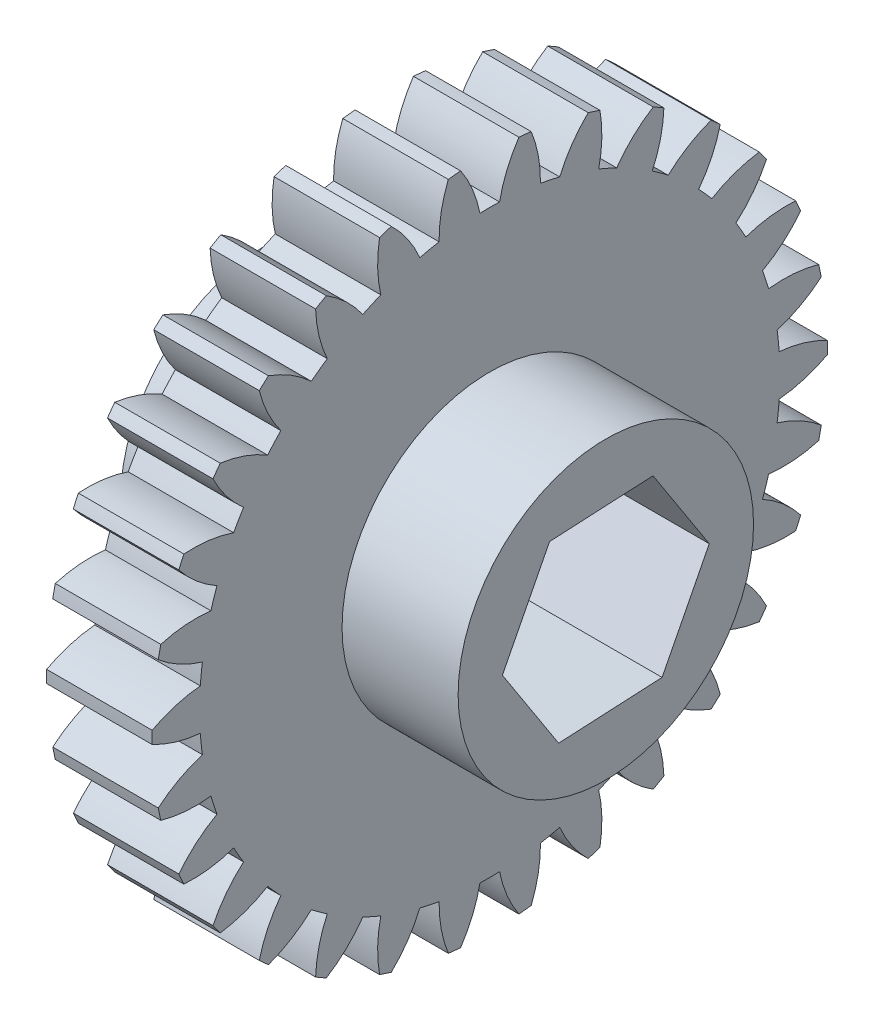
SolidWorks part; units mm, degrees
ref_plane "Plane1" through (0, 0, 0) normal (0, 0, 1) x (1, 0, 0)
ref_plane "Plane2" through (0, 0, 0) normal (0, 1, 0) x (1, 0, 0)
ref_plane "Plane3" through (0, 0, 0) normal (1, 0, 0) x (0, 0, -1)
sketch "HoldingSke" plane through (0, 0, 0) normal (0, 1, 0) x (1, 0, 0)
  line L0 (0, 0) -> (0.866, -0.5)
  line L1 (-15, 0) -> (100, 0) construction
  line L2 (0, 0) -> (-2.1039, 2.3779)
  line L3 (0, 0) -> (-11.863, 4.5341)
  line L4 (0, 0) -> (7.479, 4.318)
  line L5 (0, 0) -> (-14.9912, -5.5913)
  line L6 (0, 0) -> (-4.1448, -2.7965)
  line L7 (-2.1039, 2.3779) -> (1.3401, 18.0029)
  line L8 (-76.2, 54.61) -> (-75.9, 54.61)
  line L9 (-71.009, 38.7566) -> (-53.1078, 45.2721)
  line L10 (-76.2, 71.12) -> (104.1128, 71.12)
  line L11 (0, 0) -> (-5, 0)
  line L12 (-76.2, 101.6) -> (-76.162, 101.6)
  line L13 (24.9733, 27.94) -> (52.9518, 28.4284)
  line L14 (24.9733, 27.94) -> (24.9743, 27.94)
  line L15 (24.9733, 27.94) -> (100.4006, 29.5858)
  line L16 (-63.627, -1) -> (-12.827, -1)
  circle A0 centre (0, 0) radius 1
  circle A1 centre (0, 0) radius 7
  circle A2 centre (0, 0) radius 7
  circle A3 centre (0, 0) radius 1
  dimension "MHD" = 14
  dimension "Hub_dia" = 14
  dimension "Bore" = 2
  dimension "MBD" = 2
  dimension "Num_teeth" = 30
  dimension "Pitch" = 1
  dimension "Overall_len" = 16
  dimension "Show_teeth" = 30
  dimension "Thickness" = 5
  dimension "OAL" = 16.0001
  dimension "T_dim" = 0.3
  dimension "Ap" = 20
  dimension "H" = 19.05
  dimension "Pitch_radius" = 180.3128
  dimension "Width" = 5
  dimension "Backlash" = 0.038
  dimension "Addendum_fac" = 1
  dimension "Dedendum_fac" = 1.25
  dimension "Clearance_fac" = 0.25
  dimension "Dedendum_add" = 0.001
  dimension "Module" = 1
sketch "BasProSke" plane through (0, 0, 0) normal (0, 1, 0) x (1, 0, 0)
  line L0 (-10, 0) -> (60, 0) construction
  line L1 (0, 0) -> (0, 16)
  line L2 (0, 0) -> (5, 0)
  line L3 (5, 0) -> (5, 16)
  line L4 (5, 16) -> (0, 16)
  dimension "Thickness" = 5
  dimension "Diameter" = 32
revolve "Base-Revolve" add sketch "BasProSke" angle 360 about L0
sketch "TooCutSke" plane through (0, 0, 0) normal (1, 0, 0) x (0, 0, -1)
  line L1 (0, 0) -> (0, 107) construction
  line L2 (0, 0) -> (-0.8515, 14.9758) construction
  line L3 (0, 0) -> (-3.1323, 29.8014) construction
  line L4 (-0.8515, 14.9758) -> (-1.5661, 14.9007) construction
  arc A0 (0.4664, 13.7411) -> (-0.4664, 13.7411) centre (0, 0) ccw
  arc A1 (1.3975, 15.9644) -> (-1.3975, 15.9644) centre (0, 0) ccw
  circle A2 centre (0, 0) radius 15 construction
  circle A3 centre (0, 0) radius 14.0954 construction
  arc A4 (-0.4664, 13.7411) -> (-1.3975, 15.9644) centre (-6.3534, 12.5823) ccw
  arc A5 (1.3975, 15.9644) -> (0.4664, 13.7411) centre (6.3534, 12.5823) ccw
  dimension "Root_dia" = 27.498
  dimension "Overcut_dia" = 32.0508
  dimension "Pitch_dia" = 30
  dimension "Base_dia" = 28.1908
  dimension "Flank_rad" = 6
  dimension "Half_ang" = 6
  dimension "Half_CT" = 0.7185
extrude "ToothCut" cut sketch "TooCutSke" along normal through all
fillet "Breaks" [suppressed] radius 0.02
fillet "RootFillets" [suppressed] radius 0.251
pattern_circular "TeethCuts" count 30 every 12 about axis through (-10, 0, 0) along (1, 0, 0) of "ToothCut", "RootFillets", "Breaks"
sketch "HubNeaOneSke" plane through (0, 0, 0) normal (-1, 0, 0) x (0, 0, 1)
  circle A0 centre (0, 0) radius 7
  dimension "Diameter" = 14
extrude "HubNearOne" [suppressed] add sketch "HubNeaOneSke" along normal blind 11.0001
sketch "HubNeaBotSke" plane through (0, 0, 0) normal (-1, 0, 0) x (0, 0, 1)
  circle A0 centre (0, 0) radius 7
  dimension "Diameter" = 14
extrude "HubNearBoth" add sketch "HubNeaBotSke" along normal blind 5.5
ref_plane "FarPln" through (5, 0, 0) normal (1, 0, 0) x (0, 0, -1)
sketch "HubFarSke" plane through (5, 0, 0) normal (1, 0, 0) x (0, 0, -1)
  circle A0 centre (0, 0) radius 7
  dimension "Diameter" = 14
extrude "HubFar" add sketch "HubFarSke" along normal blind 5.5
sketch "BorSke" plane through (0, 0, 0) normal (1, 0, 0) x (0, 0, -1)
  circle A0 centre (0, 0) radius 1
  dimension "Diameter" = 2
extrude "Bore" cut sketch "BorSke" along normal mid plane 32.0001
sketch "KeySke" plane through (0, 0, 0) normal (1, 0, 0) x (0, 0, -1)
  line L0 (-0.4, 0) -> (-0.4, 1.3)
  line L1 (-0.4, 1.3) -> (0.4, 1.3)
  line L2 (0.4, 1.3) -> (0.4, 0)
  line L3 (0, 0) -> (0, 34) construction
  line L4 (-0.4, 0) -> (0.4, 0)
  dimension "Offset" = 1.3
  dimension "Width" = 0.8
extrude "Keyway" [suppressed] cut sketch "KeySke" along normal mid plane 32.0001
pattern_circular "Keyway2" [suppressed] count 2 every 90 about axis through (-10, 0, 0) along (1, 0, 0)
sketch "Sketch2" plane through (10.5, 0, 0) normal (1, 0, 0) x (0, 0, -1)
  line L1 (2.2355, 4.3687) -> (-2.6657, 4.1204)
  line L2 (-2.6657, 4.1204) -> (-4.9012, -0.2483)
  line L3 (-4.9012, -0.2483) -> (-2.2355, -4.3687)
  line L4 (-2.2355, -4.3687) -> (2.6657, -4.1204)
  line L5 (2.6657, -4.1204) -> (4.9012, 0.2483)
  line L6 (4.9012, 0.2483) -> (2.2355, 4.3687)
  circle A0 centre (0, 0) radius 4.25 construction
  dimension "D1" = 8.5
extrude "Cut-Extrude1" cut sketch "Sketch2" against normal through all
equation "' \"Module@HoldingSke\" = 6.35"
equation "' \"Num_teeth@HoldingSke\" = 12"
equation "' \"Ap@HoldingSke\" =  20"
equation "' \"Ap@HoldingSke\" = 20"
equation "' \"Width@HoldingSke\" = 0.5 * 25.4"
equation "' \"Hub_dia@HoldingSke\"= 1 * 25.4"
equation "' \"Hub_dia@HoldingSke\" = 1 * 25.4"
equation "' \"Overall_len@HoldingSke\" = 1.0 * 25.4"
equation "' \"Bore@HoldingSke\" = 0.75 * 25.4"
equation "' \"T_dim@HoldingSke\" = 0.1 * 25.4"
equation "' \"Width@KeySke\" = 0.25 * 25.4"
equation "' \"Show_teeth@HoldingSke\" = 13"
equation "' \"Backlash@HoldingSke\" = 0.009 * 25.4"
equation "' \"Addendum_fac@HoldingSke\" = 1.0"
equation "' \"Dedendum_fac@HoldingSke\" = 1.25"
equation "' \"Dedendum_add@HoldingSke\" = 0.00005 * 25.4"
equation "' \"Clearance_fac@HoldingSke\" = 0.25"
equation "\"Pitch@HoldingSke\" = 1 / \"Module@HoldingSke\""
equation "\"Overcut_dia@TooCutSke\" = (\"Num_teeth@HoldingSke\" + 2 * \"Addendum_fac@HoldingSke\") / \"Pitch@HoldingSke\" + 0.002 * 25.4"
equation "\"Pitch_dia@TooCutSke\" = \"Num_teeth@HoldingSke\" / \"Pitch@HoldingSke\""
equation "\"Base_dia@TooCutSke\" = \"Num_teeth@HoldingSke\" / \"Pitch@HoldingSke\" * cos((\"Ap@HoldingSke\"  * 3.14159265 / 180))"
equation "\"Root_dia@TooCutSke\" = (\"Num_teeth@HoldingSke\" + 2) / \"Pitch@HoldingSke\" - 2 * (\"Addendum_fac@HoldingSke\" + \"Dedendum_fac@HoldingSke\") / \"Pitch@HoldingSke\" - \"Dedendum_add@HoldingSke\" * 2"
equation "\"Half_ang@TooCutSke\" = 180 / \"Num_teeth@HoldingSke\""
equation "\"Half_CT@TooCutSke\" = \"Num_teeth@HoldingSke\" / \"Pitch@HoldingSke\" * sin((3.14159265 / 2 / \"Num_teeth@HoldingSke\")) / 2 - 7 * \"Backlash@HoldingSke\" / 4"
equation "\"Flank_rad@TooCutSke\" = \"Num_teeth@HoldingSke\" / \"Pitch@HoldingSke\" / 5"
equation "\"Radius@RootFillets\" = \"Clearance_fac@HoldingSke\" / \"Pitch@HoldingSke\" + \"Dedendum_add@HoldingSke\""
equation "\"Break_rad@Breaks\" = 0.02 / \"Pitch@HoldingSke\""
equation "\"Thickness@HoldingSke\" = \"Width@HoldingSke\""
equation "\"OAL@HoldingSke\" = \"Thickness@HoldingSke\""
equation "\"MHD@HoldingSke\" = (\"Num_teeth@HoldingSke\" + 2) / \"Pitch@HoldingSke\" - 2 * (\"Addendum_fac@HoldingSke\" + \"Dedendum_fac@HoldingSke\")  / \"Pitch@HoldingSke\" - \"Dedendum_add@HoldingSke\" * 2"
equation "\"MBD@HoldingSke\" = (\"Num_teeth@HoldingSke\" + 2) / \"Pitch@HoldingSke\" - 2 * (\"Addendum_fac@HoldingSke\" + \"Dedendum_fac@HoldingSke\")  / \"Pitch@HoldingSke\" - \"Dedendum_add@HoldingSke\" * 2 - 0.002 * 25.4"
equation "\"MHD@HoldingSke\" = ((sgn( \"MHD@HoldingSke\" - \"Hub_dia@HoldingSke\" )-1)*( \"MHD@HoldingSke\" - \"Hub_dia@HoldingSke\" ))/-2+ \"Hub_dia@HoldingSke\""
equation "\"MBD@HoldingSke\" = ((sgn( \"MBD@HoldingSke\" - \"Bore@HoldingSke\" )-1)*( \"MBD@HoldingSke\" - \"Bore@HoldingSke\" ))/-2+ \"Bore@HoldingSke\""
equation "\"OAL@HoldingSke\" = ((sgn( \"OAL@HoldingSke\" - \"Overall_len@HoldingSke\" )+1)*( \"OAL@HoldingSke\" - \"Overall_len@HoldingSke\" ))/2 + \"Overall_len@HoldingSke\" + 0.000002 * 25.4"
equation "\"Num_teeth@TeethCuts\" = int( \"Show_teeth@HoldingSke\" ) + 1"
equation "\"Num_teeth@TeethCuts\" = ((sgn( \"Num_teeth@TeethCuts\" - \"Num_teeth@HoldingSke\" )-1)*( \"Num_teeth@TeethCuts\" - \"Num_teeth@HoldingSke\" ))/-2+ \"Num_teeth@HoldingSke\""
equation "\"Num_teeth@TeethCuts\" = ((sgn( \"Num_teeth@TeethCuts\" - 2.0)+1)*( \"Num_teeth@TeethCuts\" - 2.0))/2 +2.0"
equation "\"Angle@TeethCuts\" = 360.0 / \"Num_teeth@HoldingSke\""
equation "\"Diameter@BasProSke\" = (\"Num_teeth@HoldingSke\" + 2 * \"Addendum_fac@HoldingSke\") / \"Pitch@HoldingSke\""
equation "\"Thickness@BasProSke\"  = \"Thickness@HoldingSke\""
equation "' \"Fillet_rad@BasProSke\" =  \"Thickness@HoldingSke\" * 0.05"
equation "' \"Fillet_rad@BasProSke\" = \"Thickness@HoldingSke\" * 0.05"
equation "\"MHD@HoldingSke\" = ((sgn( \"MHD@HoldingSke\" - \"Root_dia@TooCutSke\" )-1)*( \"MHD@HoldingSke\" - \"Root_dia@TooCutSke\" ))/-2+ \"Root_dia@TooCutSke\""
equation "\"Diameter@HubNeaOneSke\" = \"MHD@HoldingSke\""
equation "\"Length@HubNearOne\" = \"OAL@HoldingSke\" - \"Thickness@BasProSke\""
equation "\"Diameter@HubNeaBotSke\" = \"MHD@HoldingSke\""
equation "\"Length@HubNearBoth\" = ( \"OAL@HoldingSke\" - \"Thickness@BasProSke\" ) / 2.0"
equation "\"Thickness@FarPln\" = \"Thickness@BasProSke\""
equation "\"Diameter@HubFarSke\" = \"MHD@HoldingSke\""
equation "\"Length@HubFar\" = ( \"OAL@HoldingSke\" - \"Thickness@BasProSke\" ) / 2.0"
equation "\"Diameter@BorSke\" = \"MBD@HoldingSke\""
equation "\"D1@Bore\" = \"OAL@HoldingSke\" * 2.0"
equation "\"D1@Keyway\" = \"OAL@HoldingSke\" * 2.0"
equation "\"Offset@KeySke\" = \"T_dim@HoldingSke\" + \"MBD@HoldingSke\" / 2.0"
